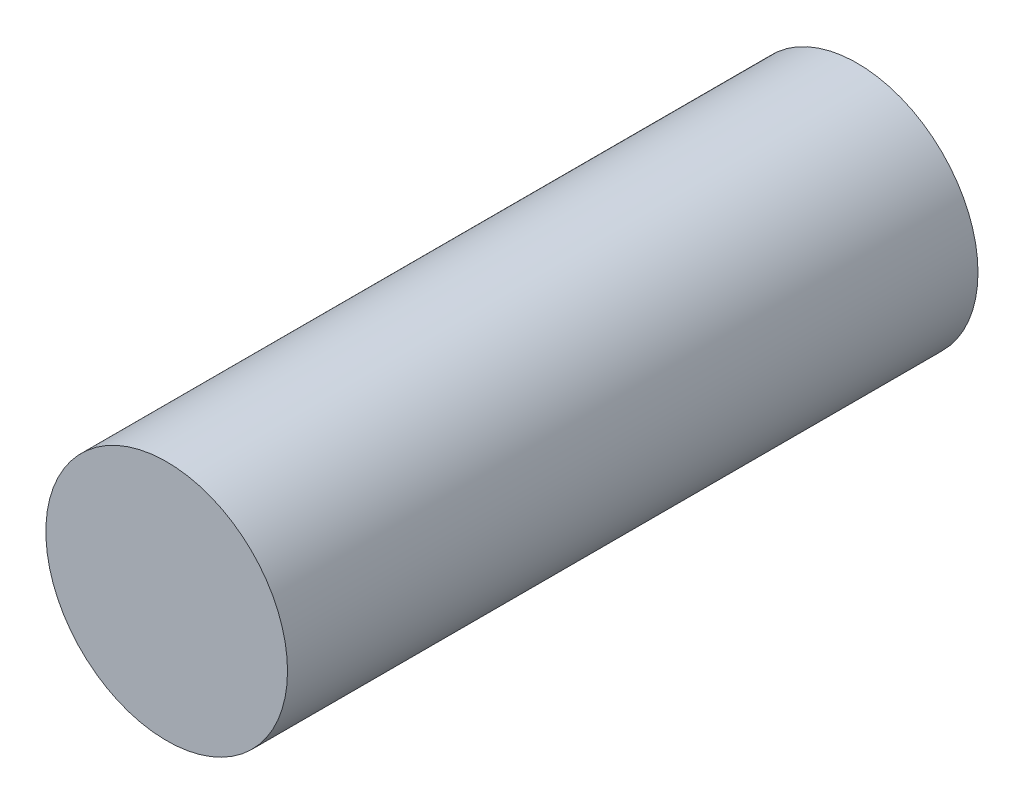
SolidWorks part; units mm, degrees
ref_plane "Front Plane" through (0, 0, 0) normal (0, 0, 1) x (1, 0, 0)
ref_plane "Top Plane" through (0, 0, 0) normal (0, 1, 0) x (1, 0, 0)
ref_plane "Right Plane" through (0, 0, 0) normal (1, 0, 0) x (0, 0, -1)
sketch "Sketch1" plane through (0, 0, 0) normal (0, 0, 1) x (1, 0, 0)
  circle A0 centre (0, 0) radius 3.5
  dimension "D1" = 7
extrude "Boss-Extrude1" add sketch "Sketch1" along normal blind 20
sketch "Sketch2" plane through (0, 0, 0) normal (0, 0, -1) x (-1, 0, 0)
  line L0 (-1.3982, 1.43) -> (1.3982, 1.43)
  arc A0 (-1.3982, 1.43) -> (1.3982, 1.43) centre (0, 0) ccw
  dimension "D1" = 4
  dimension "D2" = 1.43
extrude "Cut-Extrude1" cut sketch "Sketch2" against normal blind 10
